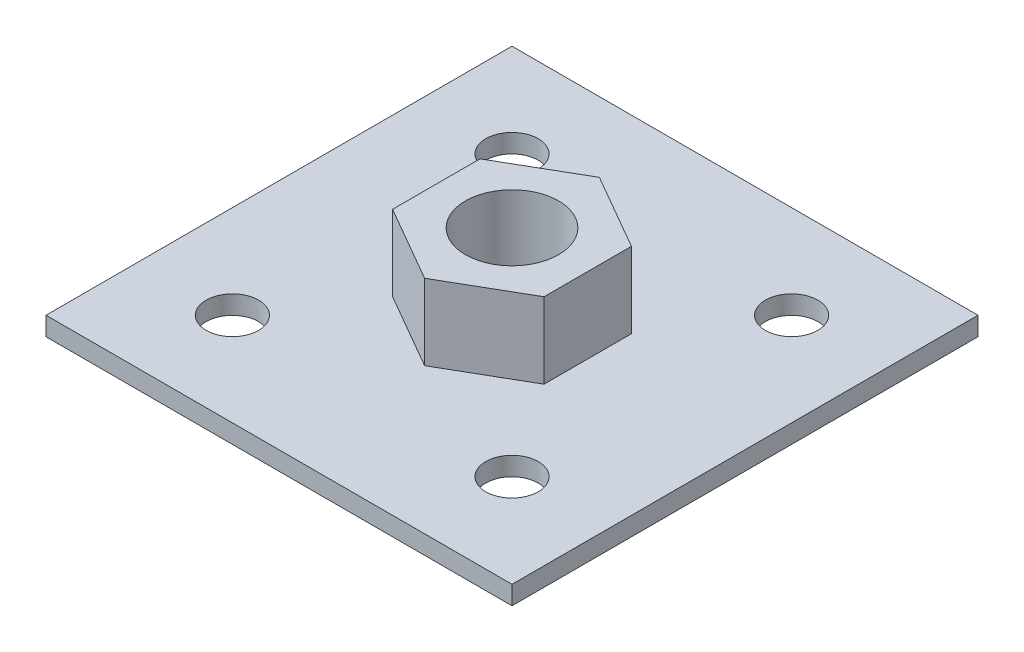
SolidWorks part; units mm, degrees
ref_plane "正面" through (0, 0, 0) normal (0, 0, 1) x (1, 0, 0)
ref_plane "平面" through (0, 0, 0) normal (0, 1, 0) x (1, 0, 0)
ref_plane "右側面" through (0, 0, 0) normal (1, 0, 0) x (0, 0, -1)
sketch "ｽｹｯﾁ1" plane through (0, 0, 0) normal (0, 1, 0) x (1, 0, 0)
  line L1 (-20, -20) -> (20, -20)
  line L2 (-20, -20) -> (-20, 20)
  line L3 (-20, 20) -> (20, 20)
  line L4 (20, -20) -> (20, 20)
  line L5 (-20, -20) -> (20, 20) construction
  line L6 (-20, 20) -> (20, -20) construction
  circle A0 centre (-12, 12) radius 2.25
  circle A1 centre (12, 12) radius 2.25
  circle A2 centre (-12, -12) radius 2.25
  circle A3 centre (12, -12) radius 2.25
  point P0 (0, 0)
  point P14 (0, 0)
  point P15 (0, 0)
  point P16 (0, 0)
  point P17 (0, 0)
  dimension "D4" = 4.5
  dimension "D1" = 40
  dimension "D2" = 40
  dimension "D3" = 24
extrude "ﾎﾞｽ - 押し出し1" add sketch "ｽｹｯﾁ1" along normal blind 1.6
sketch "ｽｹｯﾁ2" plane through (0, 1.6, 0) normal (0, 1, 0) x (1, 0, 0)
  line L0 (0, 7.5) -> (6.5, 3.7517)
  line L1 (6.5, 3.7517) -> (6.5, -3.7517)
  line L2 (6.5, -3.7517) -> (0, -7.5)
  line L3 (0, -7.5) -> (-6.5, -3.7517)
  line L4 (-6.5, -3.7517) -> (-6.5, 3.7517)
  line L5 (-6.5, 3.7517) -> (0, 7.5)
  point P6 (0, 0)
  point P7 (0, 0)
  point P9 (3.961, 2.336)
  point P10 (6.5, 0)
  point P11 (-6.5, 0)
  point P12 (0, 5.4872)
  dimension "D1" = 13
  dimension "D2" = 15
extrude "ﾎﾞｽ - 押し出し2" add sketch "ｽｹｯﾁ2" along normal blind 6.5
sketch "ｽｹｯﾁ3" plane through (0, 8.1, 0) normal (0, 1, 0) x (1, 0, 0)
  circle A0 centre (0, 0) radius 4
  dimension "D1" = 8
extrude "ｶｯﾄ - 押し出し1" cut sketch "ｽｹｯﾁ3" against normal through all
